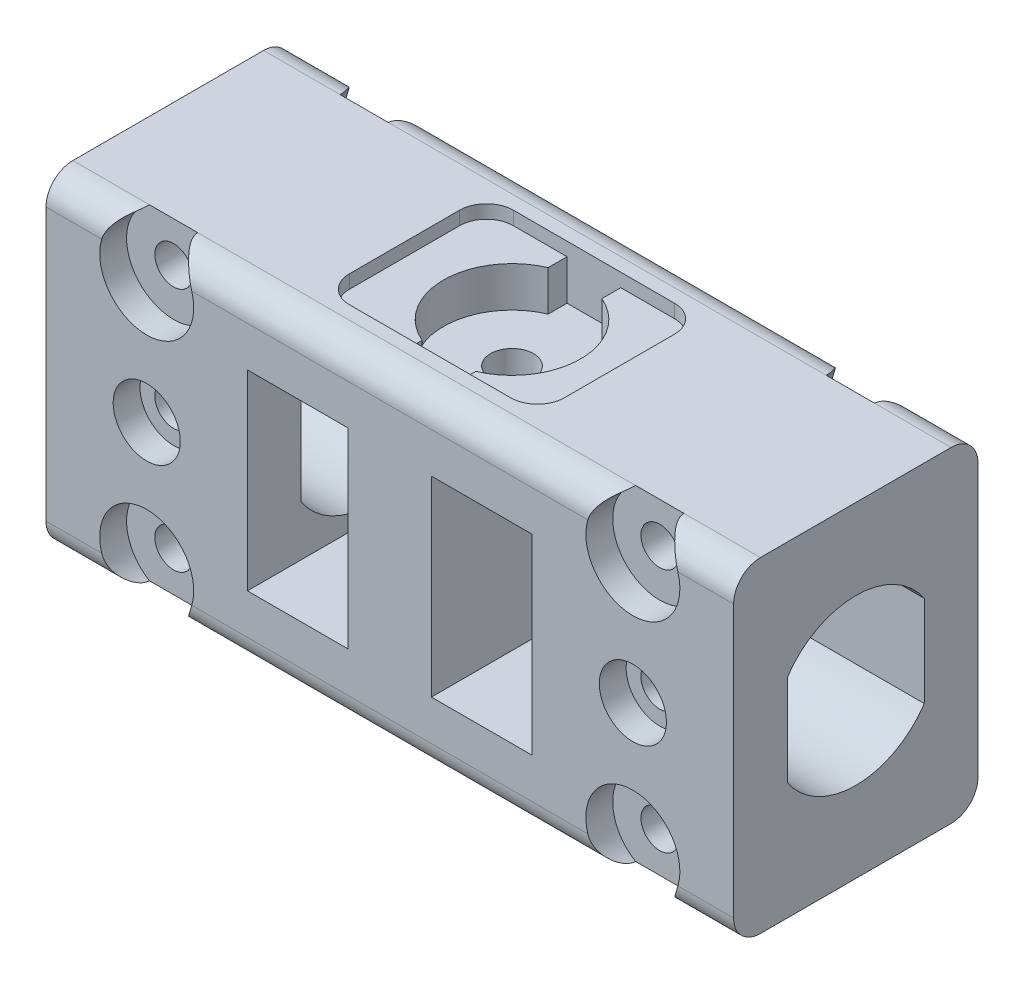
SolidWorks part; units mm, degrees
other "Marca1"
sketch "Croquis14" plane through (0, 12.125, 11.075) normal (0.4418, 0.7227, 0.5316) x (-0.8801, 0.4641, 0.1005)
ref_plane "Front Plane" through (0, 0, 0) normal (1, 0, 0) x (0, 1, 0)
ref_plane "Top Plane" through (0, 0, 0) normal (0, 0, 1) x (0, 1, 0)
ref_plane "Right Plane" through (0, 0, 0) normal (0, 1, 0) x (-1, 0, 0)
sketch "Croquis1" plane through (0, 0, 0) normal (1, 0, 0) x (0, 1, 0)
  line L0 (-3.392, 5.1) -> (3.392, 5.1)
  line L1 (3.392, -5.1) -> (-3.392, -5.1)
  line L3 (-12.125, 9.1) -> (12.125, 9.1)
  line L4 (-12.125, 9.1) -> (-12.125, -9.1)
  line L5 (-12.125, -9.1) -> (12.125, -9.1)
  line L6 (12.125, 9.1) -> (12.125, -9.1)
  arc A0 (-3.392, 5.1) -> (-3.392, -5.1) centre (0, 0) ccw
  arc A1 (3.392, -5.1) -> (3.392, 5.1) centre (0, 0) ccw
  point P10 (-6.125, 0)
  point P11 (6.125, 0)
  dimension "D1" = 12.25
  dimension "D2" = 10.2
  dimension "D3" = 6
  dimension "D4" = 6
  dimension "D5" = 4
  dimension "D6" = 4
extrude "BASE_ROTOR_1" add sketch "Croquis1" against normal blind 15
sketch "Croquis2" plane through (-15, 0, 0) normal (-1, 0, 0) x (0, -1, 0)
  line L0 (12.125, -9.1) -> (-12.125, -9.1) construction
  line L1 (-12.125, 9.1) -> (-7.125, 9.1)
  line L2 (-12.125, 9.1) -> (-12.125, -9.1)
  line L3 (-12.125, -9.1) -> (-7.125, -9.1)
  line L4 (-7.125, 9.1) -> (-7.125, -9.1)
  line L5 (-7.125, 0) -> (-6.125, 0) construction
  line L6 (12.125, 9.1) -> (7.125, 9.1)
  line L7 (12.125, 9.1) -> (12.125, -9.1)
  line L8 (12.125, -9.1) -> (7.125, -9.1)
  line L9 (7.125, 9.1) -> (7.125, -9.1)
  line L10 (6.125, 0) -> (7.125, 0) construction
  line L11 (3.392, -5.1) -> (-3.392, -5.1) construction
  line L12 (-7.125, -9.1) -> (7.125, -9.1)
  line L13 (-7.125, -9.1) -> (-7.125, -6.1)
  line L14 (-7.125, -6.1) -> (7.125, -6.1)
  line L15 (7.125, -9.1) -> (7.125, -6.1)
  arc A0 (-3.392, 5.1) -> (-3.392, -5.1) centre (0, 0) ccw construction
  arc A1 (3.392, -5.1) -> (3.392, 5.1) centre (0, 0) ccw construction
  line M19 (12.125, -9.1) -> (12.125, 9.1)
  line M20 (12.125, 9.1) -> (-12.125, 9.1)
  line M21 (-12.125, 9.1) -> (-12.125, -9.1)
  line M22 (-12.125, -9.1) -> (12.125, -9.1)
  dimension "D1" = 1
  dimension "D2" = 1
extrude "BASE_ROTOR_2" add sketch "Croquis2" along normal blind 7.5 contours L9 M20 M22 M19 | L14 L4 L9 M22 | L4 M20 M21 M22
sketch "Croquis3" plane through (0, 0, -9.1) normal (0, 0, -1) x (-1, 0, 0)
  line L0 (22.5, 12.125) -> (22.5, -12.125)
  line L1 (22.5, 12.125) -> (25.6, 12.125)
  line L2 (22.5, -12.125) -> (25.6, -12.125)
  line L3 (25.6, 12.125) -> (25.6, -12.125)
  dimension "D1" = 3.1
extrude "BASE_ROTOR_3" add sketch "Croquis3" against normal through all
sketch "Croquis4" plane through (0, 0, 9.1) normal (0, 0, 1) x (1, 0, 0)
  line L0 (-15, 0) -> (0, 0) construction
  line L1 (-15, 7.125) -> (-15, -7.125) construction
  line L2 (0, 12.125) -> (0, -12.125) construction
  line L3 (-7.5, 12.125) -> (-7.5, -12.125) construction
  line L4 (-25.6, -12.125) -> (0, -12.125) construction
  circle A0 centre (-7.5, -9.125) radius 1.4
  circle A1 centre (-7.5, 9.125) radius 1.4
  point P11 (-7.5, 0)
  dimension "D1" = 2.8
  dimension "D2" = 3
extrude "PIN_JOIN_1" cut sketch "Croquis4" against normal through all
sketch "Croquis6" plane through (0, 0, -9.1) normal (0, 0, -1) x (1, 0, 0)
  line L0 (0, 0) -> (-25.6, 0) construction
  line L3 (0, 12.125) -> (0, -12.125) construction
  line L4 (-25.6, 12.125) -> (-25.6, -12.125) construction
  circle A0 centre (-7.5, 9.125) radius 3.5
  circle A3 centre (-7.5, -9.125) radius 3.5
  dimension "D1" = 7
extrude "PIN_JOIN_2" cut sketch "Croquis6" against normal blind 2
sketch "Croquis19" plane through (0, 0, 9.1) normal (0, 0, 1) x (1, 0, 0)
  line L0 (-5.6972, -12.125) -> (-9.3028, -12.125) construction
  line L1 (-9.3028, 12.125) -> (-5.6972, 12.125) construction
  line L2 (-5.6972, -12.125) -> (-9.3028, -12.125)
  line L3 (-9.3028, 12.125) -> (-5.6972, 12.125)
  arc A0 (-5.6972, -12.125) -> (-9.3028, -12.125) centre (-7.5, -9.125) ccw construction
  arc A1 (-9.3028, 12.125) -> (-5.6972, 12.125) centre (-7.5, 9.125) ccw construction
  arc A2 (-5.6972, -12.125) -> (-9.3028, -12.125) centre (-7.5, -9.125) ccw
  arc A3 (-9.3028, 12.125) -> (-5.6972, 12.125) centre (-7.5, 9.125) ccw
extrude "PIN_JOIN_3" cut sketch "Croquis19" against normal blind 2
sketch "Croquis9" plane through (0, 0, 9.1) normal (0, 0, 1) x (1, 0, 0)
  line L0 (-15, 0) -> (0, 0) construction
  line L1 (-15, 7.125) -> (-15, -7.125) construction
  line L2 (0, 12.125) -> (0, -12.125) construction
  circle A0 centre (-7.5, 0) radius 1.4
  dimension "D1" = 2.8
extrude "PRISIONER_JOIN_1" cut sketch "Croquis9" against normal up to surface (4 mm away) up to face at (-7.5, 0, 5.1)
sketch "Croquis20" plane through (0, 0, 9.1) normal (0, 0, 1) x (1, 0, 0)
  circle A0 centre (-7.5, 0) radius 2.5
  dimension "D1" = 5
extrude "PRISIONER_JOIN_2" cut sketch "Croquis20" against normal blind 2
mirror "Simetría1" about plane through (-25.6, 12.125, 9.1) normal (-1, 0, 0) of bodies 120 110
sketch "Croquis11" plane through (0, 12.125, 0) normal (0, 1, 0) x (-1, 0, 0)
  line L0 (25.6, -9.1) -> (25.6, 9.1) construction
  line L1 (45.5028, 7.1) -> (41.8972, 7.1) construction
  line L2 (19.6, 6.1) -> (31.6, 6.1)
  line L3 (41.8972, -9.1) -> (9.3028, -9.1) construction
  line L4 (41.8972, 9.1) -> (9.3028, 9.1) construction
  line L5 (17.6, 4.1) -> (17.6, -4.1)
  line L6 (19.6, -6.1) -> (31.6, -6.1)
  line L7 (33.6, 4.1) -> (33.6, -4.1)
  line L10 (33.6, 0) -> (25.6, 0) construction
  arc A0 (17.6, -4.1) -> (19.6, -6.1) centre (19.6, -4.1) ccw
  arc A1 (31.6, -6.1) -> (33.6, -4.1) centre (31.6, -4.1) ccw
  arc A2 (31.6, 6.1) -> (33.6, 4.1) centre (31.6, 4.1) cw
  arc A3 (19.6, 6.1) -> (17.6, 4.1) centre (19.6, 4.1) ccw
  point P19 (25.6, 6.1)
  dimension "D1" = 2
  dimension "D2" = 1
  dimension "D3" = 16
extrude "BEARING_1" cut sketch "Croquis11" against normal blind 1
sketch "Croquis13" plane through (0, 11.125, 0) normal (0, 1, 0) x (-1, 0, 0)
  line L0 (25.6, -6.1) -> (25.6, 6.1) construction
  line L1 (19.6, -6.1) -> (31.6, -6.1) construction
  line L2 (31.6, 6.1) -> (19.6, 6.1) construction
  circle A0 centre (25.6, 0) radius 5.1
  point P3 (0, 0)
  point P10 (25.6, 0)
  dimension "D1" = 10.2
extrude "BEARING_2" cut sketch "Croquis13" against normal blind 3
sketch "Croquis22" plane through (0, 11.125, 0) normal (0, 1, 0) x (-1, 0, 0)
  line L0 (19.6, -6.1) -> (31.6, -6.1) construction
  line L1 (23.6, -4.6915) -> (27.6, -4.6915)
  line L2 (23.6, -4.6915) -> (23.6, -6.1)
  line L3 (23.6, -6.1) -> (27.6, -6.1)
  line L4 (27.6, -4.6915) -> (27.6, -6.1)
  line L5 (31.6, 6.1) -> (19.6, 6.1) construction
  line L6 (23.6, 6.1) -> (27.6, 6.1)
  line L7 (23.6, 6.1) -> (23.6, 4.6915)
  line L8 (23.6, 4.6915) -> (27.6, 4.6915)
  line L9 (27.6, 6.1) -> (27.6, 4.6915)
  circle A0 centre (25.6, 0) radius 5.1 construction
  point P8 (25.6, -6.1)
  point P15 (25.6, 6.1)
  dimension "D1" = 4
extrude "BEARING_3" cut sketch "Croquis22" against normal up to surface (3 mm away) up to face at (-25.6, 8.125, 5.1)
sketch "Croquis15" plane through (0, -12.125, 0) normal (0, -1, 0) x (1, 0, 0)
  line L0 (-17.6, 4.1) -> (-17.6, -4.1) construction
  line L1 (-19.6, -6.1) -> (-31.6, -6.1) construction
  line L2 (-33.6, -4.1) -> (-33.6, 4.1) construction
  line L3 (-31.6, 6.1) -> (-19.6, 6.1) construction
  line L4 (-17.6, 4.1) -> (-17.6, -4.1)
  line L5 (-19.6, -6.1) -> (-31.6, -6.1)
  line L6 (-33.6, -4.1) -> (-33.6, 4.1)
  line L7 (-31.6, 6.1) -> (-19.6, 6.1)
  arc A2 (-17.6, 4.1) -> (-19.6, 6.1) centre (-19.6, 4.1) ccw construction
  arc A3 (-19.6, -6.1) -> (-17.6, -4.1) centre (-19.6, -4.1) ccw construction
  arc A4 (-33.6, -4.1) -> (-31.6, -6.1) centre (-31.6, -4.1) ccw construction
  arc A5 (-31.6, 6.1) -> (-33.6, 4.1) centre (-31.6, 4.1) ccw construction
  arc A6 (-17.6, 4.1) -> (-19.6, 6.1) centre (-19.6, 4.1) ccw
  arc A7 (-19.6, -6.1) -> (-17.6, -4.1) centre (-19.6, -4.1) ccw
  arc A8 (-33.6, -4.1) -> (-31.6, -6.1) centre (-31.6, -4.1) ccw
  arc A9 (-31.6, 6.1) -> (-33.6, 4.1) centre (-31.6, 4.1) ccw
extrude "BEARING_4" cut sketch "Croquis15" against normal blind 1
sketch "Croquis16" plane through (0, -11.125, 0) normal (0, -1, 0) x (1, 0, 0)
  line L6 (-23.6, -6.1) -> (-23.6, -4.6915)
  line L7 (-27.6, -6.1) -> (-23.6, -6.1)
  line L8 (-27.6, -4.6915) -> (-27.6, -6.1)
  line L9 (-27.6, 6.1) -> (-27.6, 4.6915)
  line L10 (-23.6, 6.1) -> (-27.6, 6.1)
  line L11 (-23.6, 4.6915) -> (-23.6, 6.1)
  line L12 (-23.6, -6.1) -> (-23.6, -4.6915)
  line L13 (-27.6, -6.1) -> (-23.6, -6.1)
  line L14 (-27.6, -4.6915) -> (-27.6, -6.1)
  line L15 (-27.6, 6.1) -> (-27.6, 4.6915)
  line L16 (-23.6, 6.1) -> (-27.6, 6.1)
  line L17 (-23.6, 4.6915) -> (-23.6, 6.1)
  arc A4 (-23.6, -4.6915) -> (-23.6, 4.6915) centre (-25.6, 0) ccw
  arc A5 (-27.6, 4.6915) -> (-27.6, -4.6915) centre (-25.6, 0) ccw
  arc A6 (-23.6, -4.6915) -> (-23.6, 4.6915) centre (-25.6, 0) ccw
  arc A7 (-27.6, 4.6915) -> (-27.6, -4.6915) centre (-25.6, 0) ccw
  dimension "D1" = 0
extrude "BEARING_5" cut sketch "Croquis16" against normal blind 3
sketch "Croquis17" plane through (0, 8.125, 0) normal (0, 1, 0) x (-1, 0, 0)
  line L0 (25.6, -6.1) -> (25.6, 6.1) construction
  line L1 (27.6, -6.1) -> (23.6, -6.1) construction
  line L2 (23.6, 6.1) -> (27.6, 6.1) construction
  circle A0 centre (25.6, 0) radius 1.6
  point P3 (0, 0)
  point P10 (0, 0)
  dimension "D1" = 3.2
extrude "PIN_MAIN" cut sketch "Croquis17" against normal through all
fillet "FILLET_BOX" radius 2 12 edges at (-25.6, 12.125, -9.1) (-48.3514, 12.125, -9.1) (-48.3514, 12.125, 9.1) (-25.6, 12.125, 9.1) (-2.8486, 12.125, 9.1) (-2.8486, -12.125, -9.1) (-25.6, -12.125, -9.1) (-48.3514, -12.125, -9.1) (-48.3514, -12.125, 9.1) (-2.8486, -12.125, 9.1) (-25.6, -12.125, 9.1) (-2.8486, 12.125, -9.1)
